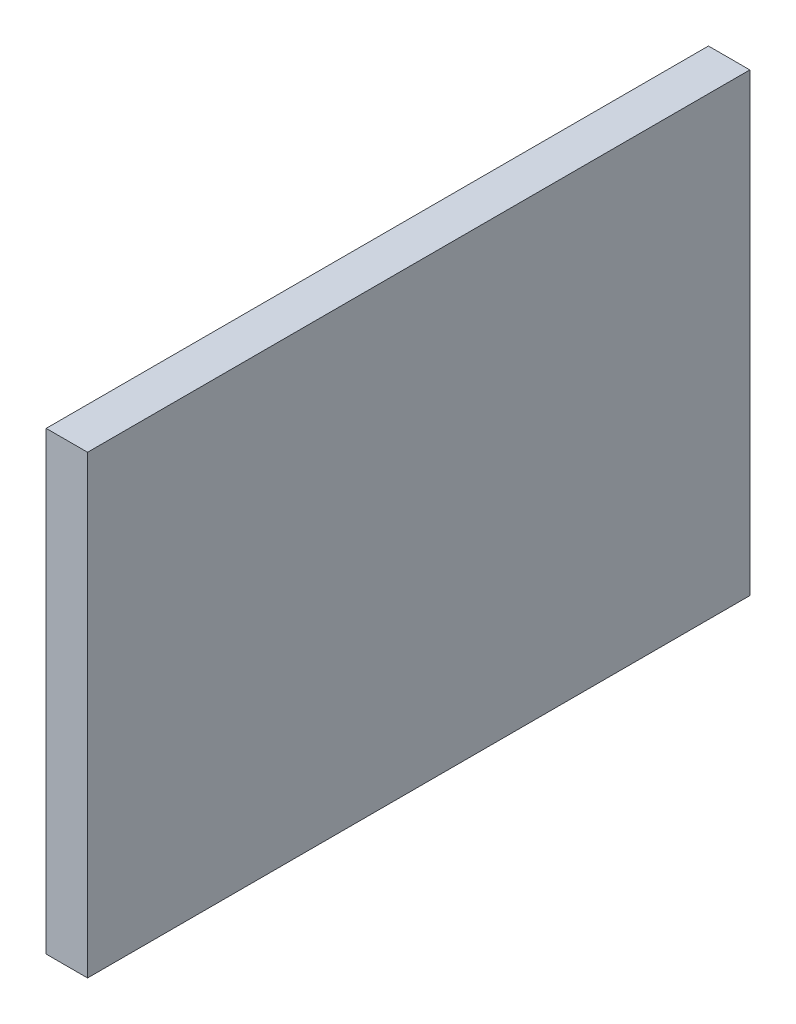
SolidWorks part; units mm, degrees
material "ASTM A36 Steel"
ref_plane "Front Plane" through (0, 0, 0) normal (0, 0, 1) x (1, 0, 0)
ref_plane "Top Plane" through (0, 0, 0) normal (0, 1, 0) x (1, 0, 0)
ref_plane "Right Plane" through (0, 0, 0) normal (1, 0, 0) x (0, 0, -1)
sketch "Sketch1" plane through (0, 0, 0) normal (1, 0, 0) x (0, 0, -1)
  line L1 (-80, -55) -> (80, -55)
  line L2 (-80, -55) -> (-80, 55)
  line L3 (-80, 55) -> (80, 55)
  line L4 (80, -55) -> (80, 55)
  line L5 (-80, -55) -> (80, 55) construction
  line L6 (-80, 55) -> (80, -55) construction
  point P0 (0, 0)
  dimension "D1" = 160
  dimension "D2" = 110
extrude "Boss-Extrude1" add sketch "Sketch1" along normal blind 10
